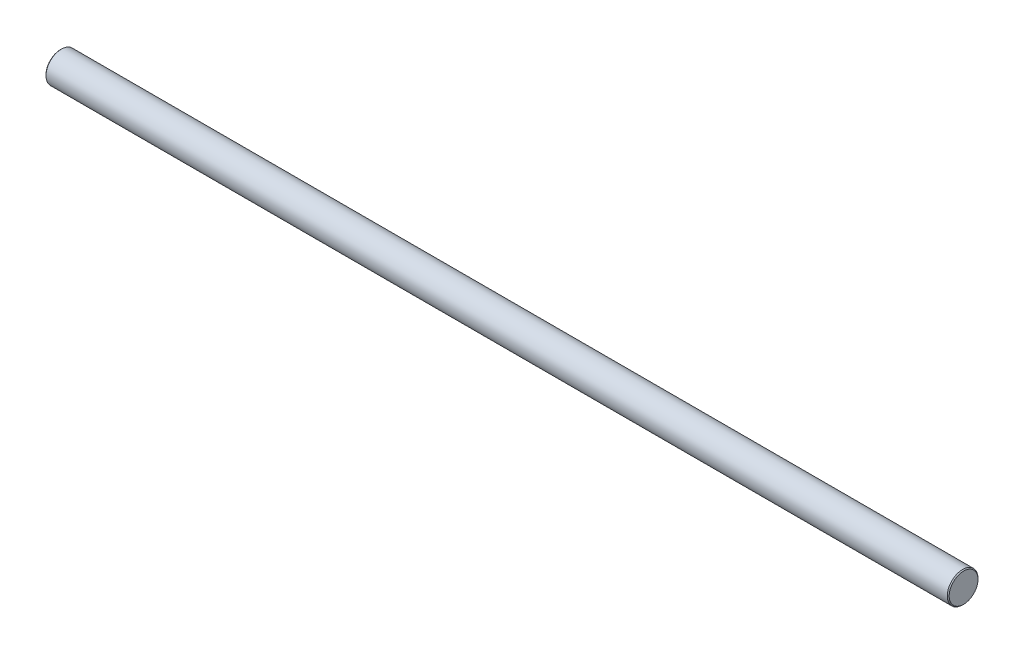
SolidWorks part; units mm, degrees
ref_plane "Front Plane" through (0, 0, 0) normal (0, 0, 1) x (1, 0, 0)
ref_plane "Top Plane" through (0, 0, 0) normal (0, 1, 0) x (1, 0, 0)
ref_plane "Right Plane" through (0, 0, 0) normal (1, 0, 0) x (0, 0, -1)
sketch "Sketch1" plane through (0, 0, 0) normal (1, 0, 0) x (0, 0, -1)
  circle A0 centre (0, 0) radius 4
  dimension "D1" = 8
extrude "Boss-Extrude1" add sketch "Sketch1" along normal mid plane 235
chamfer "Chamfer1" distance 0.25 angle 45 2 edges at (117.5, 0, -4) (-117.5, 0, -4)
